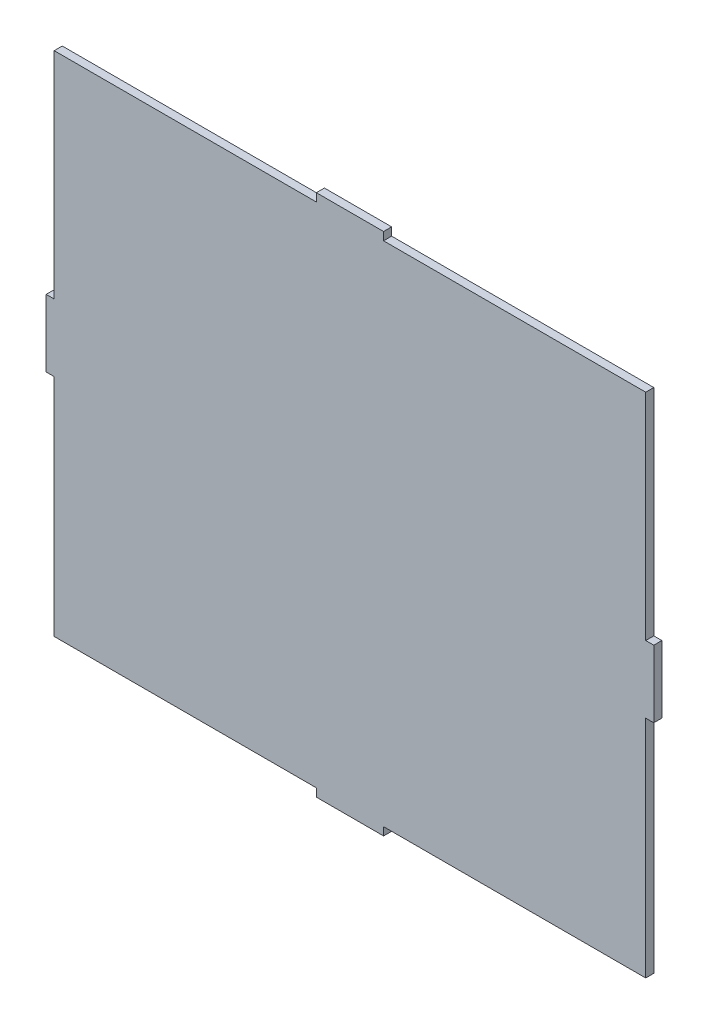
SolidWorks part; units mm, degrees
ref_plane "Спереди" through (0, 0, 0) normal (0, 0, 1) x (1, 0, 0)
ref_plane "Сверху" through (0, 0, 0) normal (0, 1, 0) x (1, 0, 0)
ref_plane "Справа" through (0, 0, 0) normal (1, 0, 0) x (0, 0, -1)
sketch "Эскиз1" plane through (0, 0, 0) normal (0, 0, 1) x (1, 0, 0)
  line L0 (-142.4909, 187.2306) -> (-44.9909, 187.2306)
  line L1 (-264.9909, 187.2306) -> (-167.4909, 187.2306)
  line L2 (-264.9909, 187.2306) -> (-264.9909, 107.2306)
  line L3 (-264.9909, -1.4694) -> (-167.4909, -1.4694)
  line L4 (-44.9909, 187.2306) -> (-44.9909, 107.2306)
  line L6 (-167.4909, 187.2306) -> (-167.4909, 190.2306)
  line L7 (-167.4909, 190.2306) -> (-142.4909, 190.2306)
  line L8 (-142.4909, 187.2306) -> (-142.4909, 190.2306)
  line L10 (-167.4909, -1.4694) -> (-167.4909, -4.4694)
  line L11 (-167.4909, -4.4694) -> (-142.4909, -4.4694)
  line L12 (-142.4909, -1.4694) -> (-142.4909, -4.4694)
  line L13 (-264.9909, 107.2306) -> (-267.9909, 107.2306)
  line L15 (-264.9909, 82.2306) -> (-267.9909, 82.2306)
  line L16 (-267.9909, 107.2306) -> (-267.9909, 82.2306)
  line L17 (-44.9909, 107.2306) -> (-41.9909, 107.2306)
  line L19 (-44.9909, 82.2306) -> (-41.9909, 82.2306)
  line L20 (-41.9909, 107.2306) -> (-41.9909, 82.2306)
  line L21 (-264.9909, 82.2306) -> (-264.9909, -1.4694)
  line L22 (-44.9909, 82.2306) -> (-44.9909, -1.4694)
  line L23 (-142.4909, -1.4694) -> (-44.9909, -1.4694)
  point P20 (0, 0)
  dimension "D1" = 188.7
  dimension "D2" = 220
  dimension "D3" = 25
  dimension "D4" = 25
  dimension "D5" = 25
  dimension "D6" = 25
  dimension "D7" = 3
  dimension "D8" = 3
  dimension "D9" = 3
  dimension "D10" = 3
  dimension "D11" = 97.5
  dimension "D12" = 97.5
  dimension "D13" = 80
  dimension "D14" = 80
extrude "Бобышка-Вытянуть1" add sketch "Эскиз1" along normal blind 3
